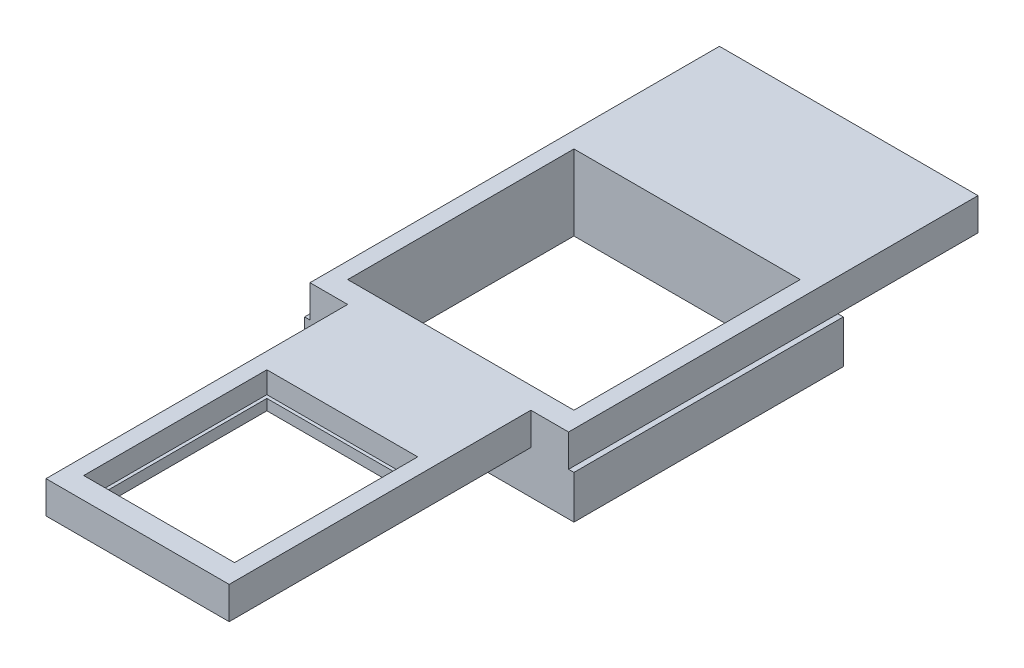
SolidWorks part; units mm, degrees
ref_plane "Front" through (0, 0, 0) normal (0, 0, 1) x (1, 0, 0)
ref_plane "Top" through (0, 0, 0) normal (0, 1, 0) x (1, 0, 0)
ref_plane "Right" through (0, 0, 0) normal (1, 0, 0) x (0, 0, -1)
sketch "Sketch1" plane through (0, 0, 0) normal (0, 1, 0) x (1, 0, 0)
  line L1 (-12.5, -12.5) -> (12.5, -12.5)
  line L2 (-12.5, -12.5) -> (-12.5, 12.5)
  line L3 (-12.5, 12.5) -> (12.5, 12.5)
  line L4 (12.5, -12.5) -> (12.5, 12.5)
  line L5 (-12.5, -12.5) -> (12.5, 12.5) construction
  line L6 (-12.5, 12.5) -> (12.5, -12.5) construction
  point P0 (0, 0)
  dimension "D1" = 25
extrude "Boss-Extrude1" add sketch "Sketch1" along normal blind 4
sketch "Sketch2" plane through (0, 4, 0) normal (0, 1, 0) x (1, 0, 0)
  line L0 (-12.5, -12.5) -> (12.5, -12.5) construction
  line L1 (-12, 25.5) -> (12, 25.5)
  line L2 (-12, 25.5) -> (-12, -12.5)
  line L3 (-12, -12.5) -> (12, -12.5)
  line L4 (12, 25.5) -> (12, -12.5)
  point P4 (0, -12.5)
  point P5 (0, -12.5)
  dimension "D1" = 38
  dimension "D2" = 24
extrude "Boss-Extrude2" add sketch "Sketch2" along normal blind 3
sketch "Sketch3" plane through (0, 0, -25.5) normal (0, 0, -1) x (-1, 0, 0)
  line L1 (-10, 4) -> (10, 4)
  line L2 (-10, 4) -> (-10, 6.25)
  line L3 (-10, 6.25) -> (10, 6.25)
  line L4 (10, 4) -> (10, 6.25)
  line L5 (-12, 4) -> (12, 4) construction
  point P4 (0, 4)
  point P6 (0, 4)
  dimension "D1" = 2.25
  dimension "D2" = 20
extrude "Cut-Extrude1" cut sketch "Sketch3" against normal up to surface (13 mm away) up to face at (0, 2.6667, -12.5)
sketch "Sketch4" plane through (0, 0, 12.5) normal (0, 0, 1) x (1, 0, 0)
  line L0 (-12, 7) -> (12, 7) construction
  line L1 (-8.5, 7) -> (8.5, 7)
  line L2 (-8.5, 7) -> (-8.5, 4)
  line L3 (-8.5, 4) -> (8.5, 4)
  line L4 (8.5, 7) -> (8.5, 4)
  point P4 (0, 7)
  point P5 (0, 7)
  dimension "D1" = 17
  dimension "D2" = 3
extrude "Boss-Extrude3" add sketch "Sketch4" along normal blind 28
sketch "Sketch5" plane through (0, 7, 0) normal (0, 1, 0) x (1, 0, 0)
  line L0 (8.5, -40.5) -> (-8.5, -40.5) construction
  line L1 (-7, -21.5) -> (7, -21.5)
  line L2 (-7, -21.5) -> (-7, -38.5)
  line L3 (-7, -38.5) -> (7, -38.5)
  line L4 (7, -21.5) -> (7, -38.5)
  line L5 (8.5, -40.5) -> (8.5, -12.5) construction
  point P4 (0, -38.5)
  dimension "D1" = 1.5
  dimension "D2" = 17
  dimension "D3" = 2
extrude "Cut-Extrude2" cut sketch "Sketch5" against normal up to next
sketch "Sketch6" plane through (-10, 0, 0) normal (1, 0, 0) x (0, 0, -1)
  line L0 (25.5, 4) -> (25.5, 6.25) construction
  line L1 (25.5, 4) -> (25.5, 6.25)
  line L2 (25.5, 6.25) -> (24.5, 6.25)
  line L3 (24.5, 6.25) -> (24.5, 4)
  line L4 (24.5, 4) -> (25.5, 4)
  dimension "D1" = 1
extrude "Boss-Extrude4" add sketch "Sketch6" along normal up to next
sketch "Sketch7" plane through (-12, 0, 0) normal (-1, 0, 0) x (0, 0, 1)
  line L0 (-25.5, 4) -> (-12.5, 4) construction
  line L1 (-19.5, 4) -> (-17.5, 4)
  line L2 (-19.5, 4) -> (-19.5, 6.25)
  line L3 (-19.5, 6.25) -> (-17.5, 6.25)
  line L4 (-17.5, 4) -> (-17.5, 6.25)
  line L5 (-12.5, 6.25) -> (-24.5, 6.25) construction
  line L6 (-12.5, 6.25) -> (-24.5, 6.25) construction
  point P0 (-12.5, 4)
  dimension "D1" = 5
  dimension "D2" = 2
extrude "Cut-Extrude3" cut sketch "Sketch7" against normal up to next
sketch "Sketch9" plane through (0, 0, 0) normal (0, -1, 0) x (1, 0, 0)
  line L8 (10.5, -10.5) -> (10.5, 10.5)
  line L9 (-10.5, -10.5) -> (10.5, -10.5)
  line L10 (-10.5, 10.5) -> (-10.5, -10.5)
  line L11 (10.5, 10.5) -> (-10.5, 10.5)
  line L12 (10.5, -10.5) -> (10.5, 10.5)
  line L13 (-10.5, -10.5) -> (10.5, -10.5)
  line L14 (-10.5, 10.5) -> (-10.5, -10.5)
  line L15 (10.5, 10.5) -> (-10.5, 10.5)
  dimension "D1" = 2
extrude "Cut-Extrude4" cut sketch "Sketch9" against normal up to next
sketch "Sketch11" plane through (0, 4, 0) normal (0, -1, 0) x (1, 0, 0)
  line L0 (-7, 38.5) -> (-7, 21.5) construction
  line L1 (7, 38.5) -> (-7, 38.5) construction
  line L2 (7, 21.5) -> (7, 38.5) construction
  line L3 (-7, 21.5) -> (7, 21.5) construction
  line L4 (-7, 38.5) -> (-7, 21.5)
  line L5 (7, 38.5) -> (-7, 38.5)
  line L6 (7, 21.5) -> (7, 38.5)
  line L7 (-7, 21.5) -> (7, 21.5)
  line L8 (-6.7, 38.2) -> (-6.7, 21.8)
  line L9 (-6.7, 21.8) -> (6.7, 21.8)
  line L10 (6.7, 21.8) -> (6.7, 38.2)
  line L11 (6.7, 38.2) -> (-6.7, 38.2)
  dimension "D1" = 0.3
extrude "Boss-Extrude5" add sketch "Sketch11" against normal blind 1
